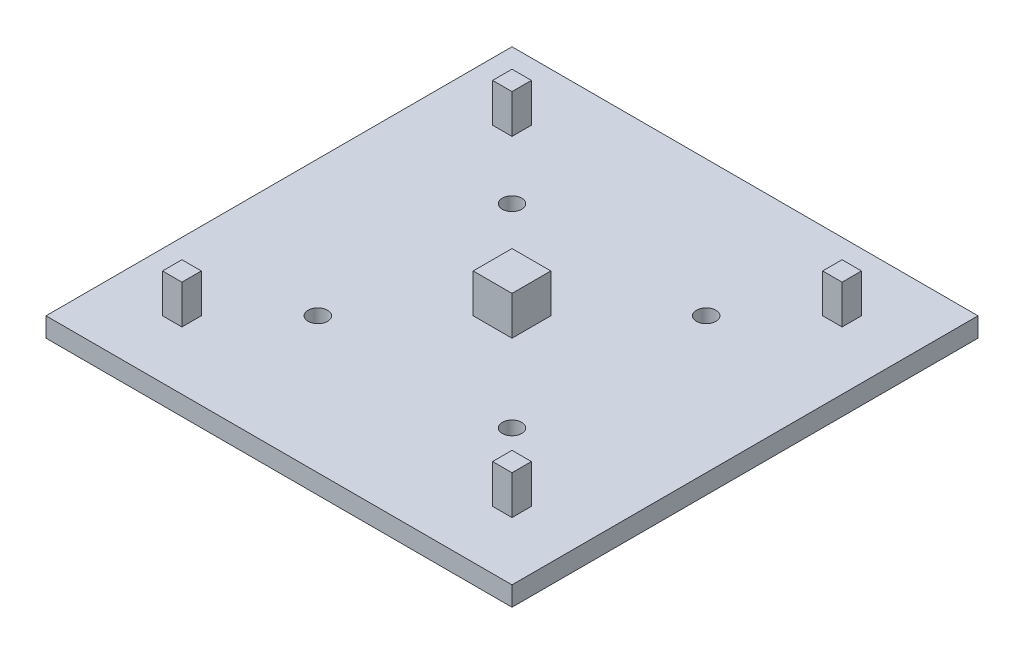
SolidWorks part; units mm, degrees
ref_plane "Front Plane" through (0, 0, 0) normal (0, 0, 1) x (1, 0, 0)
ref_plane "Top Plane" through (0, 0, 0) normal (0, 1, 0) x (1, 0, 0)
ref_plane "Right Plane" through (0, 0, 0) normal (1, 0, 0) x (0, 0, -1)
sketch "Sketch1" plane through (0, 0, 0) normal (0, 1, 0) x (1, 0, 0)
  line L1 (-60, 60) -> (60, 60)
  line L2 (-60, 60) -> (-60, -60)
  line L3 (-60, -60) -> (60, -60)
  line L4 (60, 60) -> (60, -60)
  line L5 (-60, 60) -> (60, -60) construction
  line L6 (-60, -60) -> (60, 60) construction
  point P0 (0, 0)
extrude "Boss-Extrude1" add sketch "Sketch1" along normal blind 5
sketch "Sketch2" plane through (0, 5, 0) normal (0, 1, 0) x (1, 0, 0)
  circle A0 centre (-25, 25) radius 2.5
extrude "Cut-Extrude1" cut sketch "Sketch2" against normal blind 5
sketch "Sketch3" plane through (0, 5, 0) normal (0, 1, 0) x (1, 0, 0)
  circle A0 centre (25, 25) radius 2.5
extrude "Cut-Extrude2" cut sketch "Sketch3" against normal blind 5
sketch "Sketch4" plane through (0, 5, 0) normal (0, 1, 0) x (1, 0, 0)
  circle A0 centre (25, -25) radius 2.5
extrude "Cut-Extrude3" cut sketch "Sketch4" against normal blind 5
sketch "Sketch5" plane through (0, 5, 0) normal (0, 1, 0) x (1, 0, 0)
  circle A0 centre (-25, -25) radius 2.5
extrude "Cut-Extrude4" cut sketch "Sketch5" against normal blind 5
sketch "Sketch6" plane through (0, 5, 0) normal (0, 1, 0) x (1, 0, 0)
  line L1 (-5, 5) -> (5, 5)
  line L2 (-5, 5) -> (-5, -5)
  line L3 (-5, -5) -> (5, -5)
  line L4 (5, 5) -> (5, -5)
  line L5 (-5, 5) -> (5, -5) construction
  line L6 (-5, -5) -> (5, 5) construction
  point P0 (0, 0)
extrude "Boss-Extrude2" add sketch "Sketch6" along normal blind 10
sketch "Sketch10" plane through (0, 5, 0) normal (0, 1, 0) x (1, 0, 0)
  line L1 (40, 45) -> (45, 45)
  line L2 (40, 45) -> (40, 40)
  line L3 (40, 40) -> (45, 40)
  line L4 (45, 45) -> (45, 40)
  line L5 (40, 45) -> (45, 40) construction
  line L6 (40, 40) -> (45, 45) construction
  point P0 (42.5, 42.5)
extrude "Boss-Extrude4" add sketch "Sketch10" along normal blind 10
sketch "Sketch11" plane through (0, 5, 0) normal (0, 1, 0) x (1, 0, 0)
  line L1 (-45, 45) -> (-40, 45)
  line L2 (-45, 45) -> (-45, 40)
  line L3 (-45, 40) -> (-40, 40)
  line L4 (-40, 45) -> (-40, 40)
  line L5 (-45, 45) -> (-40, 40) construction
  line L6 (-45, 40) -> (-40, 45) construction
  point P0 (-42.5, 42.5)
extrude "Boss-Extrude5" add sketch "Sketch11" along normal blind 10
sketch "Sketch12" plane through (0, 5, 0) normal (0, 1, 0) x (1, 0, 0)
  line L1 (40, -40) -> (45, -40)
  line L2 (40, -40) -> (40, -45)
  line L3 (40, -45) -> (45, -45)
  line L4 (45, -40) -> (45, -45)
  line L5 (40, -40) -> (45, -45) construction
  line L6 (40, -45) -> (45, -40) construction
  point P0 (42.5, -42.5)
extrude "Boss-Extrude6" add sketch "Sketch12" along normal blind 10
sketch "Sketch13" plane through (0, 5, 0) normal (0, 1, 0) x (1, 0, 0)
  line L1 (-45, -40) -> (-40, -40)
  line L2 (-45, -40) -> (-45, -45)
  line L3 (-45, -45) -> (-40, -45)
  line L4 (-40, -40) -> (-40, -45)
  line L5 (-45, -40) -> (-40, -45) construction
  line L6 (-45, -45) -> (-40, -40) construction
  point P0 (-42.5, -42.5)
extrude "Boss-Extrude7" add sketch "Sketch13" along normal blind 10
